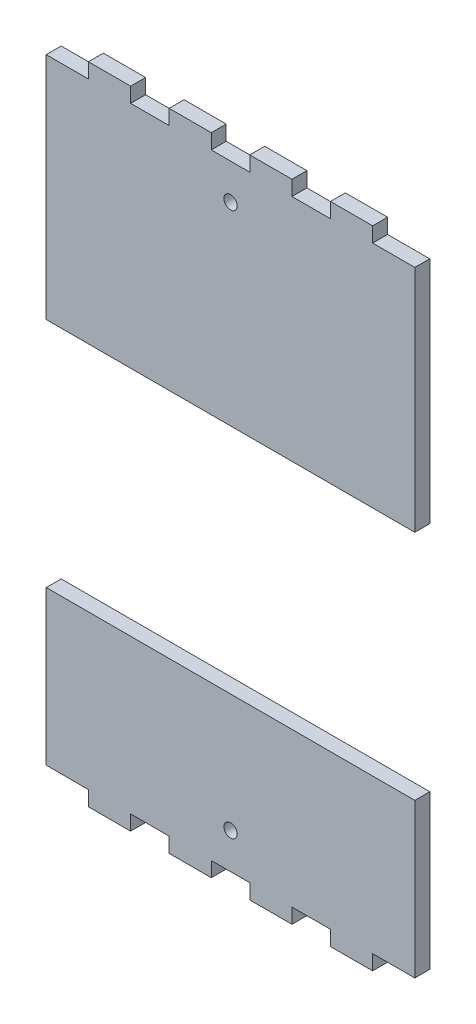
SolidWorks part; units mm, degrees
ref_plane "Front Plane" through (0, 0, 0) normal (0, 0, 1) x (1, 0, 0)
ref_plane "Top Plane" through (0, 0, 0) normal (0, 1, 0) x (1, 0, 0)
ref_plane "Right Plane" through (0, 0, 0) normal (1, 0, 0) x (0, 0, -1)
sketch "Sketch1" plane through (0, 0, 0) normal (0, 0, 1) x (1, 0, 0)
  line L1 (0, 0) -> (110.9218, 0)
  line L2 (0, 0) -> (0, 185.1914)
  line L3 (0, 185.1914) -> (110.9218, 185.1914)
  line L4 (110.9218, 0) -> (110.9218, 185.1914)
  dimension "D1" = 110.9218
  dimension "D2" = 185.1914
extrude "Boss-Extrude1" add sketch "Sketch1" along normal blind 4.4958
sketch "Sketch2" plane through (0, 0, 4.4958) normal (0, 0, 1) x (1, 0, 0)
  line L0 (110.9218, 185.1914) -> (0, 185.1914) construction
  line L1 (12.7, 185.1914) -> (25.4, 185.1914)
  line L2 (12.7, 185.1914) -> (12.7, 189.6872)
  line L3 (12.7, 189.6872) -> (25.4, 189.6872)
  line L4 (25.4, 185.1914) -> (25.4, 189.6872)
  line L5 (0, 185.1914) -> (0, 0) construction
  line L6 (36.9739, 185.1914) -> (36.9739, 189.6872)
  line L7 (36.9739, 185.1914) -> (49.6739, 185.1914)
  line L8 (49.6739, 185.1914) -> (49.6739, 189.6872)
  line L9 (36.9739, 189.6872) -> (49.6739, 189.6872)
  line L10 (61.2479, 185.1914) -> (61.2479, 189.6872)
  line L11 (61.2479, 185.1914) -> (73.9479, 185.1914)
  line L12 (73.9479, 185.1914) -> (73.9479, 189.6872)
  line L13 (61.2479, 189.6872) -> (73.9479, 189.6872)
  line L14 (85.5218, 185.1914) -> (85.5218, 189.6872)
  line L15 (85.5218, 185.1914) -> (98.2218, 185.1914)
  line L16 (98.2218, 185.1914) -> (98.2218, 189.6872)
  line L17 (85.5218, 189.6872) -> (98.2218, 189.6872)
  line L18 (110.9218, 0) -> (110.9218, 185.1914) construction
  line L19 (0, 92.5957) -> (110.9218, 92.5957) construction
  line L20 (85.5218, 0) -> (98.2218, 0)
  line L21 (98.2218, 0) -> (98.2218, -4.4958)
  line L22 (85.5218, -4.4958) -> (98.2218, -4.4958)
  line L23 (85.5218, 0) -> (85.5218, -4.4958)
  line L24 (61.2479, 0) -> (73.9479, 0)
  line L25 (73.9479, 0) -> (73.9479, -4.4958)
  line L26 (61.2479, -4.4958) -> (73.9479, -4.4958)
  line L27 (61.2479, 0) -> (61.2479, -4.4958)
  line L28 (36.9739, 0) -> (49.6739, 0)
  line L29 (49.6739, 0) -> (49.6739, -4.4958)
  line L30 (36.9739, -4.4958) -> (49.6739, -4.4958)
  line L31 (36.9739, 0) -> (36.9739, -4.4958)
  line L32 (12.7, -4.4958) -> (25.4, -4.4958)
  line L33 (25.4, 0) -> (25.4, -4.4958)
  line L34 (12.7, 0) -> (25.4, 0)
  line L35 (12.7, 0) -> (12.7, -4.4958)
  dimension "D1" = 12.7
  dimension "D2" = 4.4958
  dimension "D3" = 12.7
  dimension "D5" = 12.7
  dimension "D4" = 4
extrude "Boss-Extrude2" add sketch "Sketch2" against normal blind 4.4958
sketch "Sketch3" plane through (0, 0, 4.4958) normal (0, 0, 1) x (1, 0, 0)
  line L0 (110.9218, 0) -> (110.9218, 185.1914) construction
  line L1 (-3.3782, 116.1542) -> (110.9218, 116.1542)
  line L2 (-3.3782, 116.1542) -> (-3.3782, 46.3042)
  line L3 (-3.3782, 46.3042) -> (110.9218, 46.3042)
  line L4 (110.9218, 116.1542) -> (110.9218, 46.3042)
  line L6 (61.2479, -4.4958) -> (73.9479, -4.4958) construction
  dimension "D1" = 69.85
  dimension "D2" = 114.3
  dimension "D3" = 50.8
extrude "Cut-Extrude1" cut sketch "Sketch3" against normal through all
sketch "Sketch4" plane through (0, 0, 0) normal (0, 0, -1) x (-1, 0, 0)
  line L0 (-61.2479, 185.1914) -> (-49.6739, 185.1914) construction
  line L2 (-36.9739, -4.4958) -> (-49.6739, -4.4958) construction
  circle A0 centre (-55.4609, 174.4472) radius 2
  circle A1 centre (-55.4609, 10.7442) radius 2
  point P6 (-55.4609, 185.1914)
  dimension "D1" = 4
  dimension "D2" = 10.7442
  dimension "D3" = 15.24
extrude "Cut-Extrude2" cut sketch "Sketch4" against normal through all
